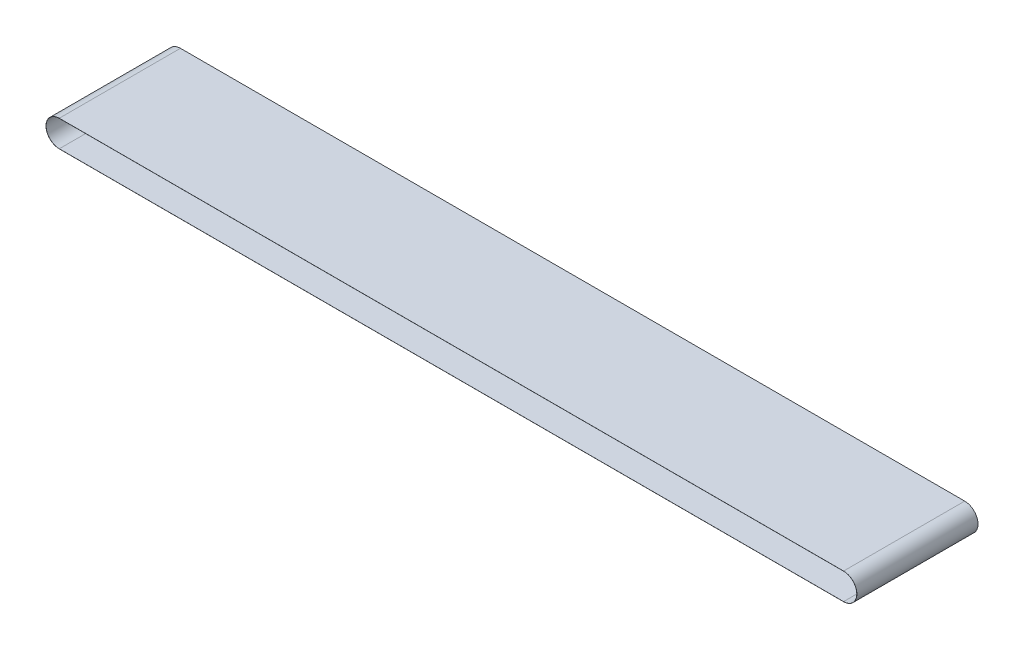
SolidWorks part; units mm, degrees
other "标注1"
sketch "草图1"
other "标注2"
sketch "草图2" plane through (-226.2, 226.2, 762.5) normal (-0.1592, 0.935, 0.3169) x (0.9798, 0.1105, 0.1664)
material "Rubber"
ref_plane "Front Plane" through (0, 0, 0) normal (0, 0, 1) x (1, 0, 0)
ref_plane "Top Plane" through (0, 0, 0) normal (0, 1, 0) x (1, 0, 0)
ref_plane "Right Plane" through (0, 0, 0) normal (1, 0, 0) x (0, 0, -1)
sketch "Sketch1" plane through (0, 0, 0) normal (0, 0, 1) x (1, 0, 0)
  line L0 (0, 0) -> (9873.28, 0) construction
  line L1 (0, 166) -> (9873.28, 166)
  line L2 (0, -166) -> (9873.28, -166)
  line L3 (0, -167.2) -> (9873.28, -167.2)
  line L4 (0, 167.2) -> (9873.28, 167.2)
  arc A0 (0, 166) -> (0, -166) centre (0, 0) ccw
  arc A1 (9873.28, -166) -> (9873.28, 166) centre (9873.28, 0) ccw
  arc A2 (0, 167.2) -> (0, -167.2) centre (0, 0) ccw
  arc A3 (9873.28, -167.2) -> (9873.28, 167.2) centre (9873.28, 0) ccw
  dimension "Overall_Length" = 9873.28
  dimension "D2" = 332
  dimension "D3" = 1.2
extrude "Boss-Extrude1" add sketch "Sketch1" along normal mid plane 1525
sketch "草图3" plane through (0, 0, 762.5) normal (0, 0, 1) x (1, 0, 0)
  circle A0 centre (0, 0) radius 250
  circle A1 centre (5000, 0) radius 250
  point P2 (0, 0)
  point P3 (0, 0)
  point P4 (0, 0)
  point P5 (0, 0)
  dimension "D1" = 5000
  dimension "D2" = 500
  dimension "D3" = 500
